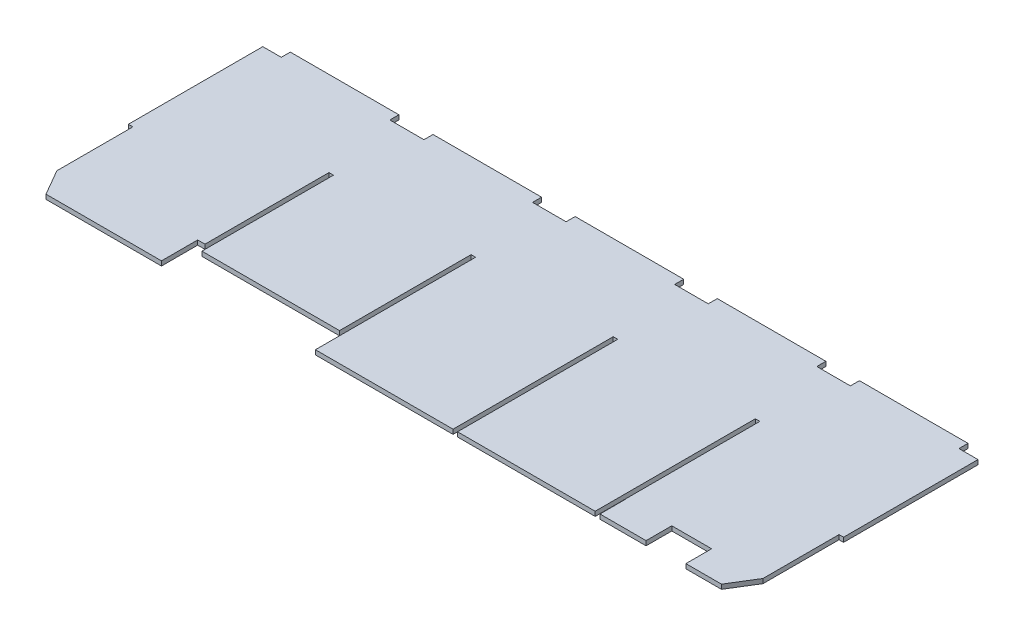
SolidWorks part; units mm, degrees
material "6061-T6 (SS)"
ref_plane "X-Y Datum" through (0, 0, 0) normal (0, 0, 1) x (1, 0, 0)
ref_plane "X-Z Datum" through (0, 0, 0) normal (0, 1, 0) x (1, 0, 0)
ref_plane "Y-Z Datum" through (0, 0, 0) normal (1, 0, 0) x (0, 0, -1)
sketch "Sketch1" plane through (0, 0, 0) normal (0, 1, 0) x (1, 0, 0)
  line L1 (0, 0) -> (495.5921, 0)
  line L2 (0, 0) -> (0, 147.6985)
  line L3 (0, 147.6985) -> (495.5921, 147.6985)
  line L4 (495.5921, 0) -> (495.5921, 147.6985)
extrude "Boss-Extrude1" add sketch "Sketch1" along normal blind 3.175
sketch "Sketch2" plane through (0, 0, -147.6985) normal (0, 0, -1) x (-1, 0, 0)
  line L0 (-495.5921, 0) -> (-495.5921, 3.175) construction
  line L1 (-495.5921, 0) -> (0, 0) construction
  line L2 (0, 0) -> (0, 3.175) construction
  line L3 (-495.5921, 3.175) -> (0, 3.175) construction
  line L4 (-485.4029, 0) -> (-485.4029, 3.175)
  line L5 (-485.4029, 0) -> (-409.2029, 0)
  line L6 (-409.2029, 0) -> (-409.2029, 3.175)
  line L7 (-485.4029, 3.175) -> (-409.2029, 3.175)
  line L8 (-385.6495, 0) -> (-385.6495, 3.175)
  line L9 (-385.6495, 0) -> (-309.4495, 0)
  line L10 (-309.4495, 0) -> (-309.4495, 3.175)
  line L11 (-385.6495, 3.175) -> (-309.4495, 3.175)
  line L12 (-285.8961, 0) -> (-285.8961, 3.175)
  line L13 (-285.8961, 0) -> (-209.6961, 0)
  line L14 (-209.6961, 0) -> (-209.6961, 3.175)
  line L15 (-285.8961, 3.175) -> (-209.6961, 3.175)
  line L16 (-186.1426, 0) -> (-186.1426, 3.175)
  line L17 (-186.1426, 0) -> (-109.9426, 0)
  line L18 (-109.9426, 0) -> (-109.9426, 3.175)
  line L19 (-186.1426, 3.175) -> (-109.9426, 3.175)
  line L20 (-85.9955, 0) -> (-85.9955, 3.175)
  line L21 (-85.9955, 0) -> (-9.7955, 0)
  line L22 (-9.7955, 0) -> (-9.7955, 3.175)
  line L23 (-85.9955, 3.175) -> (-9.7955, 3.175)
extrude "Boss-Extrude2" add sketch "Sketch2" along normal blind 6.35
sketch "Sketch3" plane through (0, 3.175, 0) normal (0, 1, 0) x (1, 0, 0)
  line L0 (109.9426, 147.6985) -> (85.9955, 147.6985) construction
  line L5 (96.3816, 53.3324) -> (99.5566, 242.0645) construction
  line L6 (96.3816, 242.0645) -> (99.5566, 53.3324) construction
  line L7 (209.6961, 147.6985) -> (186.1426, 147.6985) construction
  line L12 (196.3318, 53.3324) -> (199.5068, 242.0645) construction
  line L13 (196.3318, 242.0645) -> (199.5068, 53.3324) construction
  line L14 (309.4495, 147.6985) -> (285.8961, 147.6985) construction
  line L19 (296.0853, 53.3324) -> (299.2603, 242.0645) construction
  line L20 (296.0853, 242.0645) -> (299.2603, 53.3324) construction
  line L21 (409.2029, 147.6985) -> (385.6495, 147.6985) construction
  line L26 (395.8387, 53.3324) -> (399.0137, 242.0645) construction
  line L27 (395.8387, 242.0645) -> (399.0137, 53.3324) construction
  line L28 (0, 73.8492) -> (586.0795, 73.8492) construction
  line L29 (395.8387, -94.3661) -> (399.0137, -94.3661)
  line L30 (399.0137, 94.3661) -> (399.0137, -94.3661)
  line L31 (395.8387, 94.3661) -> (399.0137, 94.3661)
  line L32 (395.8387, 94.3661) -> (395.8387, -94.3661)
  line L33 (296.0853, -94.3661) -> (299.2603, -94.3661)
  line L34 (299.2603, 94.3661) -> (299.2603, -94.3661)
  line L35 (296.0853, 94.3661) -> (299.2603, 94.3661)
  line L36 (296.0853, 94.3661) -> (296.0853, -94.3661)
  line L37 (196.3318, -94.3661) -> (199.5068, -94.3661)
  line L38 (199.5068, 94.3661) -> (199.5068, -94.3661)
  line L39 (196.3318, 94.3661) -> (199.5068, 94.3661)
  line L40 (196.3318, 94.3661) -> (196.3318, -94.3661)
  line L41 (96.5797, -94.3661) -> (99.7547, -94.3661)
  line L42 (99.7547, 94.3661) -> (99.7547, -94.3661)
  line L43 (96.5797, 94.3661) -> (99.7547, 94.3661)
  line L44 (96.5797, 94.3661) -> (96.5797, -94.3661)
  point P0 (97.9691, 147.6985)
  point P7 (197.9193, 147.6985)
  point P14 (297.6728, 147.6985)
  point P21 (397.4262, 147.6985)
extrude "Cut-Extrude1" cut sketch "Sketch3" against normal blind 3.175
sketch "Sketch4" plane through (0, 3.175, 0) normal (0, 1, 0) x (1, 0, 0)
  line L0 (247.7961, 150.8735) -> (247.7961, -31.2363) construction
  line L1 (0, 147.6985) -> (-3.175, 147.6985)
  line L2 (0, 147.6985) -> (0, 53.3324)
  line L3 (0, 53.3324) -> (-3.175, 53.3324)
  line L4 (-3.175, 147.6985) -> (-3.175, 53.3324)
  line L5 (495.5921, 53.3324) -> (498.7671, 53.3324)
  line L6 (498.7671, 147.6985) -> (498.7671, 53.3324)
  line L7 (495.5921, 147.6985) -> (498.7671, 147.6985)
  line L8 (495.5921, 147.6985) -> (495.5921, 53.3324)
extrude "Boss-Extrude3" add sketch "Sketch4" against normal through all
sketch "Sketch5" plane through (0, 3.175, 0) normal (0, 1, 0) x (1, 0, 0)
  line L5 (99.7547, 0) -> (99.7547, -18.0442) construction
  line L6 (196.3318, 0) -> (196.3318, -18.0442) construction
  line L7 (199.5068, 0) -> (199.5068, -18.0442)
  line L8 (296.0853, 0) -> (296.0853, -18.0442)
  line L9 (299.2603, 0) -> (299.2603, -18.0442)
  line L10 (395.8387, 0) -> (395.8387, -18.0442)
  line L14 (299.2603, 0) -> (395.8387, 0)
  line L15 (299.2603, -18.0442) -> (395.8387, -18.0442)
  line L16 (199.5068, 0) -> (296.0853, 0)
  line L17 (199.5068, -18.0442) -> (296.0853, -18.0442)
  line L18 (99.7547, 0) -> (196.3318, 0) construction
  line L19 (99.7547, -18.0442) -> (196.3318, -18.0442) construction
  line L20 (429.9839, -18.0442) -> (431.5604, -18.0442)
  line L27 (247.7961, 154.0485) -> (247.7961, 184.2448) construction
  line L28 (495.5921, 0) -> (484.4686, -18.0442)
  line L29 (423.6339, 0) -> (399.2105, 0)
  line L31 (429.9839, -18.0442) -> (399.2105, -18.0442)
  line L32 (399.2105, 0) -> (399.2105, -18.0442)
  line L33 (484.4686, 0) -> (459.5004, 0)
  line L35 (484.4686, -18.0442) -> (459.5004, -18.0442)
  line L37 (0, 0) -> (10.4178, -18.0442)
  line L38 (96.5797, 0) -> (0, 0)
  line L39 (96.5797, 0) -> (96.5797, -18.0442)
  line L40 (96.5797, -18.0442) -> (10.4178, -18.0442)
  line L43 (431.5604, -18.0442) -> (431.5604, 0)
  line L46 (484.4686, 0) -> (495.5921, 0)
  line L48 (423.6339, 0) -> (431.5604, 0)
  line L50 (459.5004, -18.0442) -> (459.5004, 0)
  dimension "D1" = 32.3499
  dimension "D2" = 27.94
extrude "Boss-Extrude4" add sketch "Sketch5" against normal through all
fillet "Fillet1" [suppressed] radius 1
sketch "Sketch6" plane through (0, 3.175, 0) normal (0, 1, 0) x (1, 0, 0)
  line L0 (196.3318, 94.3661) -> (196.3318, 0) construction
  line L1 (99.7547, 0) -> (196.3318, 0)
  line L2 (99.7547, 0) -> (99.7547, 2.032)
  line L3 (99.7547, 2.032) -> (196.3318, 2.032)
  line L4 (196.3318, 0) -> (196.3318, 2.032)
extrude "Cut-Extrude2" cut sketch "Sketch6" against normal through all
sketch "Sketch7" plane through (0, 3.175, 0) normal (0, 1, 0) x (1, 0, 0)
  line L1 (98.0673, -21.5117) -> (91.4639, -21.5117)
  line L2 (98.0673, -21.5117) -> (98.0673, 7.3558)
  line L3 (98.0673, 7.3558) -> (91.4639, 7.3558)
  line L4 (91.4639, -21.5117) -> (91.4639, 7.3558)
  point P4 (99.0408, -17.9472)
  point P5 (99.8081, -21.7795)
  point P6 (98.0673, -21.5117)
extrude "Cut-Extrude3" cut sketch "Sketch7" against normal through all
